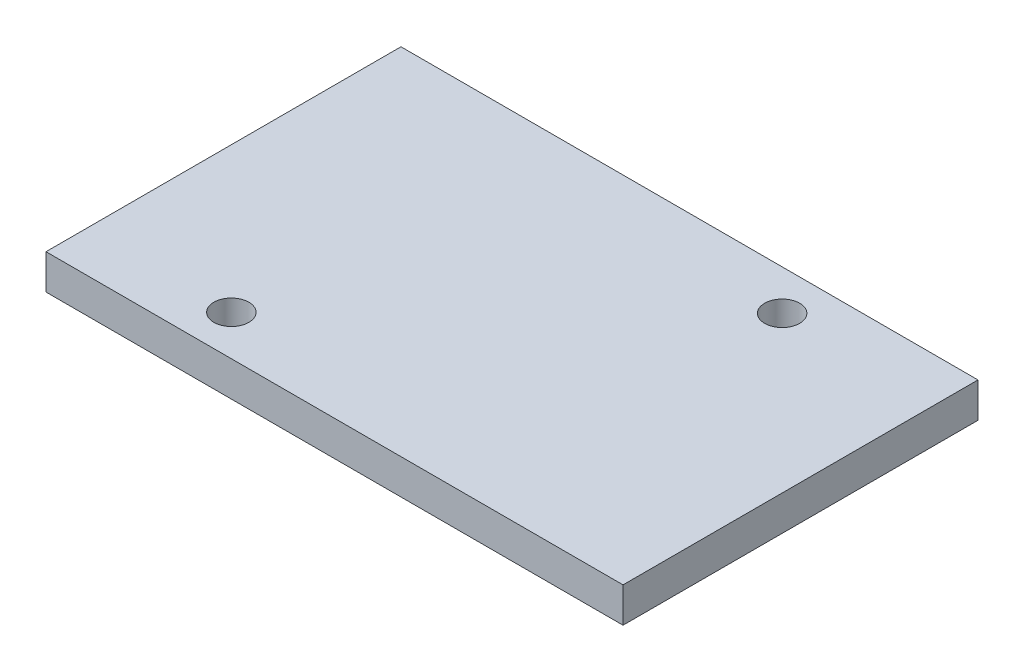
SolidWorks part; units mm, degrees
material "A-Glass Fiber"
ref_plane "Front Plane" through (0, 0, 0) normal (0, 0, 1) x (1, 0, 0)
ref_plane "Top Plane" through (0, 0, 0) normal (0, 1, 0) x (1, 0, 0)
ref_plane "Right Plane" through (0, 0, 0) normal (1, 0, 0) x (0, 0, -1)
sketch "Sketch1" plane through (0, 0, 0) normal (0, 1, 0) x (1, 0, 0)
  line L1 (-118.2696, 28.3538) -> (-85.2696, 28.3538)
  line L2 (-118.2696, 28.3538) -> (-118.2696, 8.0538)
  line L3 (-118.2696, 8.0538) -> (-85.2696, 8.0538)
  line L4 (-85.2696, 28.3538) -> (-85.2696, 8.0538)
  circle A0 centre (-109.9696, 10.3538) radius 1
  circle A1 centre (-94.1696, 26.0538) radius 1
  dimension "D4" = 2
  dimension "D5" = 2
  dimension "D1" = 20.3
  dimension "D2" = 33
  dimension "D3" = 8.3
  dimension "D6" = 2.3
  dimension "D7" = 8.9
  dimension "D8" = 2.3
extrude "Boss-Extrude1" add sketch "Sketch1" along normal blind 2
